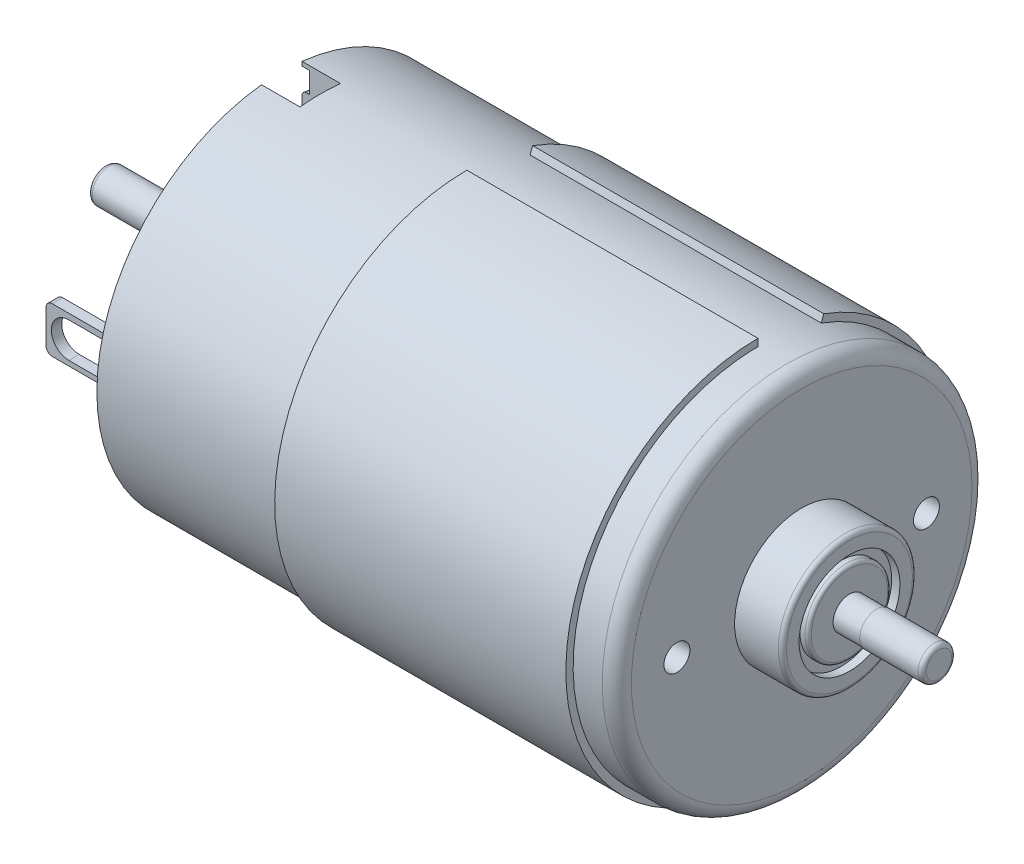
SolidWorks part; units mm, degrees
ref_plane "Front Plane" through (0, 0, 0) normal (0, 0, 1) x (1, 0, 0)
ref_plane "Top Plane" through (0, 0, 0) normal (0, 1, 0) x (1, 0, 0)
ref_plane "Right Plane" through (0, 0, 0) normal (1, 0, 0) x (0, 0, -1)
sketch "Sketch1" plane through (0, 0, 0) normal (1, 0, 0) x (0, 0, -1)
  circle A0 centre (0, 0) radius 17.78
extrude "Extrude1" add sketch "Sketch1" along normal blind 50
sketch "Sketch2" plane through (50, 0, 0) normal (1, 0, 0) x (0, 0, -1)
  circle A0 centre (0, 0) radius 6.45
extrude "Extrude2" add sketch "Sketch2" along normal blind 4.6
sketch "Sketch3" plane through (54.6, 0, 0) normal (1, 0, 0) x (0, 0, -1)
  circle A0 centre (0, 0) radius 1.58
extrude "Extrude3" add sketch "Sketch3" along normal blind 2.6
fillet "Fillet1" radius 1.4 1 edges at (50, 0, -17.78)
sketch "Sketch4" plane through (0, 0, 0) normal (-1, 0, 0) x (0, 0, 1)
  circle A0 centre (0, 0) radius 6.475
extrude "Extrude4" add sketch "Sketch4" along normal blind 3
sketch "Sketch5" plane through (-3, 0, 0) normal (-1, 0, 0) x (0, 0, 1)
  circle A0 centre (0, 0) radius 3.95
  circle A1 centre (0, 0) radius 2.9
extrude "Extrude5" add sketch "Sketch5" along normal blind 1
chamfer "Chamfer1" distance 0.8 angle 45 1 edges at (-4, 0, 3.95)
sketch "Sketch6" plane through (-3, 0, 0) normal (-1, 0, 0) x (0, 0, 1)
  circle A0 centre (0, 0) radius 1.58
extrude "Extrude6" add sketch "Sketch6" along normal blind 8
sketch "Sketch7" plane through (54.6, 0, 0) normal (1, 0, 0) x (0, 0, -1)
  circle A0 centre (0, 0) radius 4.85
  circle A1 centre (0, 0) radius 3.98
extrude "Extrude7" cut sketch "Sketch7" against normal blind 0.8
fillet "Fillet2" radius 0.3 1 edges at (54.6, 0, -3.98)
fillet "Fillet3" radius 0.4 1 edges at (54.6, 0, -6.45)
sketch "Sketch8" plane through (0, 0, 0) normal (-1, 0, 0) x (0, 0, 1)
  line L1 (0, 15.38) -> (0, -15.38) construction
  line L2 (-8.972, -12.4919) -> (8.972, -12.4919)
  line L3 (-8.972, -12.4919) -> (-8.972, 12.4919)
  line L4 (-8.972, 12.4919) -> (8.972, 12.4919)
  line L5 (8.972, -12.4919) -> (8.972, 12.4919)
  line L6 (-8.972, -12.4919) -> (8.972, 12.4919) construction
  line L7 (-8.972, 12.4919) -> (8.972, -12.4919) construction
  circle A0 centre (0, 0) radius 17.38
  circle A1 centre (0, 0) radius 15.38
  circle A2 centre (0, 0) radius 17.78 construction
  dimension "D1" = 17.9439
  dimension "D2" = 2
  dimension "D3" = 0.4
extrude "Extrude9" cut sketch "Sketch8" against normal blind 0.7 contours L3 A1 | A0 A1 | L5 A1
fillet "Fillet4" radius 0.4 5 edges at (0, 0, -6.475) (0, 0, 8.972) (0, 15.38, 0) (0, -15.38, 0) (0, 0, -8.972)
sketch "Sketch11" plane through (0, 0, 0) normal (-1, 0, 0) x (0, 0, 1)
  line L0 (0, -20.3904) -> (0, 28.4689) construction
  line L1 (-2.95, 19.0412) -> (2.95, 19.0412)
  line L2 (-2.95, 19.0412) -> (-2.95, 13.1401)
  line L3 (-2.95, 13.1401) -> (2.95, 13.1401)
  line L4 (2.95, 19.0412) -> (2.95, 13.1401)
  line L5 (-1.95, -13.7401) -> (1.95, -18.8623) construction
  line L6 (-21.1725, 0) -> (23.0165, 0) construction
  line L7 (-3.0332, -17.5194) -> (3.0332, -17.5194)
  line L8 (2.95, -19.0412) -> (2.95, -13.1401)
  line L9 (-2.95, -13.1401) -> (2.95, -13.1401)
  line L10 (-2.95, -19.0412) -> (-2.95, -13.1401)
  line L11 (-2.95, -19.0412) -> (2.95, -19.0412)
  line L12 (-1.95, 18.8623) -> (1.95, 18.8623)
  line L13 (-1.95, 18.8623) -> (-1.95, 13.7401)
  line L14 (-1.95, 13.7401) -> (1.95, 13.7401)
  line L15 (1.95, 18.8623) -> (1.95, 13.7401)
  line L16 (-1.95, 18.8623) -> (1.95, 13.7401) construction
  line L17 (-1.95, 13.7401) -> (1.95, 18.8623) construction
  line L18 (-1.95, -18.8623) -> (1.95, -13.7401) construction
  line L19 (0, 20.3904) -> (0, -28.4689) construction
  line L20 (1.95, -18.8623) -> (1.95, -13.7401)
  line L21 (-1.95, -13.7401) -> (1.95, -13.7401)
  line L22 (-1.95, -18.8623) -> (-1.95, -13.7401)
  line L23 (-1.95, -18.8623) -> (1.95, -18.8623)
  line L24 (2.95, -19.0412) -> (2.95, -13.1401)
  line L25 (-2.95, -13.1401) -> (2.95, -13.1401)
  line L26 (-2.95, -19.0412) -> (-2.95, -13.1401)
  line L27 (-2.95, -19.0412) -> (2.95, -19.0412)
  point P7 (0, 16.3012)
  point P27 (0, -16.3012)
  arc M2 (-8.572, -12.285) -> (8.572, -12.285) centre (0, 0) ccw
  arc M4 (8.572, 12.285) -> (-8.572, 12.285) centre (0, 0) ccw
  dimension "D1" = 5.9
  dimension "D2" = 2.95
  dimension "D3" = 1
  dimension "D4" = 0.6
extrude "Extrude11" cut sketch "Sketch11" against normal blind 3.7 contours L15 L12 L13 M4 | L15 L13 L14 M4 | L22 L7 L20 M2 | L22 L20 L21 M2 | L22 L23 L20 L7
sketch "Sketch13" plane through (0.7, 0, 0) normal (-1, 0, 0) x (0, 0, 1)
  line L0 (25.4225, 0) -> (-19.8791, 0) construction
  line L1 (11.2225, -5.97) -> (16.3225, -5.97)
  line L2 (11.2225, -5.97) -> (11.2225, 5.97)
  line L3 (11.2225, 5.97) -> (16.3225, 5.97)
  line L4 (16.3225, -5.97) -> (16.3225, 5.97)
  line L5 (11.2225, -5.97) -> (16.3225, 5.97) construction
  line L6 (11.2225, 5.97) -> (16.3225, -5.97) construction
  line L7 (11.9725, 5) -> (15.5725, 5)
  line L8 (11.9725, 5) -> (11.9725, -5)
  line L9 (11.9725, -5) -> (15.5725, -5)
  line L10 (15.5725, 5) -> (15.5725, -5)
  line L11 (11.9725, 5) -> (15.5725, -5) construction
  line L12 (11.9725, -5) -> (15.5725, 5) construction
  line L13 (0, 20.1635) -> (0, -20.37) construction
  line L14 (-11.9725, -5) -> (-15.5725, 5) construction
  line L15 (-11.9725, 5) -> (-15.5725, -5) construction
  line L16 (-11.2225, 5.97) -> (-16.3225, -5.97) construction
  line L17 (-11.2225, -5.97) -> (-16.3225, 5.97) construction
  line L18 (-15.5725, 5) -> (-15.5725, -5)
  line L19 (-11.9725, -5) -> (-15.5725, -5)
  line L20 (-11.9725, 5) -> (-11.9725, -5)
  line L21 (-11.9725, 5) -> (-15.5725, 5)
  line L22 (-16.3225, -5.97) -> (-16.3225, 5.97)
  line L23 (-11.2225, 5.97) -> (-16.3225, 5.97)
  line L24 (-11.2225, -5.97) -> (-11.2225, 5.97)
  line L25 (-11.2225, -5.97) -> (-16.3225, -5.97)
  arc A0 (1.95, -17.2703) -> (1.95, 17.2703) centre (0, 0) ccw construction
  arc A1 (16.3225, 5.97) -> (17.38, 0) centre (0, 0) ccw
  arc A2 (-16.3225, 5.97) -> (-17.38, 0) centre (0, 0) cw
  point P0 (13.7725, 0)
  point P8 (13.7725, 0)
  point P18 (24.7787, 5)
  point P21 (16.3225, -5.97)
  point P31 (-13.7725, 0)
  arc M2 (1.95, -17.2703) -> (1.95, 17.2703) centre (0, 0) ccw
  dimension "D1" = 5.1
  dimension "D2" = 3.6
  dimension "D3" = 10
  dimension "D4" = 11.94
  dimension "D5" = 0
extrude "Extrude12" add sketch "Sketch13" along normal blind 0.7 contours L4 M2 | L1 L4 L3 L2 L7 L10 L9 L8 | L25 L24 L23 L22 L21 L20 L19 L18 | L22 A1
sketch "Sketch14" plane through (0.7, 0, 0) normal (-1, 0, 0) x (0, 0, 1)
  line L0 (-24.3673, 0) -> (35.6636, 0) construction
  line L1 (13.7725, 2.2) -> (14.7725, 2.2)
  line L2 (13.7725, 2.2) -> (13.7725, -2.2)
  line L3 (13.7725, -2.2) -> (14.7725, -2.2)
  line L4 (14.7725, 2.2) -> (14.7725, -2.2)
  line L5 (13.7725, 2.2) -> (14.7725, -2.2) construction
  line L6 (13.7725, -2.2) -> (14.7725, 2.2) construction
  line L7 (15.5725, 5) -> (15.5725, -5) construction
  line L8 (0, 24.6078) -> (0, -24.5764) construction
  line L9 (-13.7725, -2.2) -> (-14.7725, 2.2) construction
  line L10 (-13.7725, 2.2) -> (-14.7725, -2.2) construction
  line L11 (-14.7725, 2.2) -> (-14.7725, -2.2)
  line L12 (-13.7725, -2.2) -> (-14.7725, -2.2)
  line L13 (-13.7725, 2.2) -> (-13.7725, -2.2)
  line L14 (-13.7725, 2.2) -> (-14.7725, 2.2)
  point P0 (14.2725, 0)
  point P16 (-14.2725, 0)
  dimension "D1" = 1
  dimension "D2" = 4.4
  dimension "D3" = 0
  dimension "D4" = 0.8
extrude "Extrude13" add sketch "Sketch14" along normal blind 8.6
fillet "Fillet5" radius 0.6 4 edges at (-7.9, -2.2, -14.2725) (-7.9, 2.2, -14.2725) (-7.9, -2.2, 14.2725) (-7.9, 2.2, 14.2725)
sketch "Sketch15" plane through (0, 0, -14.7725) normal (0, 0, -1) x (-1, 0, 0)
  line L0 (-3.3897, 0) -> (11.6139, 0) construction
  line L1 (5.7, 0) -> (2.7, 0) construction
  line L2 (5.7, -1.6846) -> (2.7, -1.6846)
  line L3 (5.7, 1.6846) -> (2.7, 1.6846)
  line L4 (0, -17.6727) -> (0, 17.6727) construction
  arc A0 (5.7, -1.6846) -> (5.7, 1.6846) centre (5.7, 0) ccw
  arc A1 (2.7, 1.6846) -> (2.7, -1.6846) centre (2.7, 0) ccw
  point P5 (4.2, 0)
  dimension "D1" = 3
  dimension "D2" = 4.2
sketch "Sketch17" plane through (50, 0, 0) normal (1, 0, 0) x (0, 0, -1)
  line L0 (-21.6095, 0) -> (22.9353, 0) construction
  line L1 (0, 19.0906) -> (0, -19.8861) construction
  circle A0 centre (12, 0) radius 1.25
  circle A2 centre (-12, 0) radius 1.25
  dimension "D1" = 12
extrude "Extrude16" cut sketch "Sketch17" against normal blind 5.8 contours A2 | A0
sketch "Sketch18" plane through (-11, 0, 0) normal (-1, 0, 0) x (0, 0, 1)
  circle A0 centre (0, 0) radius 1.625
extrude "Extrude17" add sketch "Sketch18" along normal blind 6
sketch "Sketch19" plane through (57.2, 0, 0) normal (1, 0, 0) x (0, 0, -1)
  circle A0 centre (0, 0) radius 1.625
extrude "Extrude18" add sketch "Sketch19" along normal blind 6
fillet "Fillet6" radius 0.4 1 edges at (63.2, 0, -1.625)
fillet "Fillet7" radius 0.4 1 edges at (-17, 0, 1.625)
sketch "Sketch21" plane through (0, 0, 0) normal (0, 0, 1) x (1, 0, 0)
  line L0 (-19.3307, 0) -> (70.1243, 0) construction
  line L1 (48.6, 17.78) -> (3.7, 17.78) construction
  line L2 (17.8, 17.78) -> (45.8, 17.78)
  line L3 (17.8, 17.78) -> (17.8, 18.48)
  line L4 (17.8, 18.48) -> (45.8, 18.48)
  line L5 (45.8, 17.78) -> (45.8, 18.48)
  line L6 (50, -16.38) -> (50, 16.38) construction
  dimension "D1" = 0.7
  dimension "D2" = 28
  dimension "D3" = 4.2
revolve "Revolve1" add sketch "Sketch21" angle 340 about L0
sketch "Sketch22" plane through (0, 0, 14.7725) normal (0, 0, 1) x (1, 0, 0)
  line L0 (-8.2216, -0.0401) -> (6.782, -0.0401) construction
  line L1 (-2.7, -0.0401) -> (-5.7, -0.0401) construction
  line L2 (-2.7, -1.7248) -> (-5.7, -1.7248)
  line L3 (-2.7, 1.6445) -> (-5.7, 1.6445)
  line L4 (0, 17.6727) -> (0, -17.6727) construction
  arc A0 (-2.7, -1.7248) -> (-2.7, 1.6445) centre (-2.7, -0.0401) ccw
  arc A1 (-5.7, 1.6445) -> (-5.7, -1.7248) centre (-5.7, -0.0401) ccw
  point P5 (-4.2, -0.0401)
  dimension "D1" = 3
  dimension "D2" = 4.2
extrude "Extrude20" cut sketch "Sketch15" against normal blind 1
extrude "Extrude21" cut sketch "Sketch22" against normal blind 1
